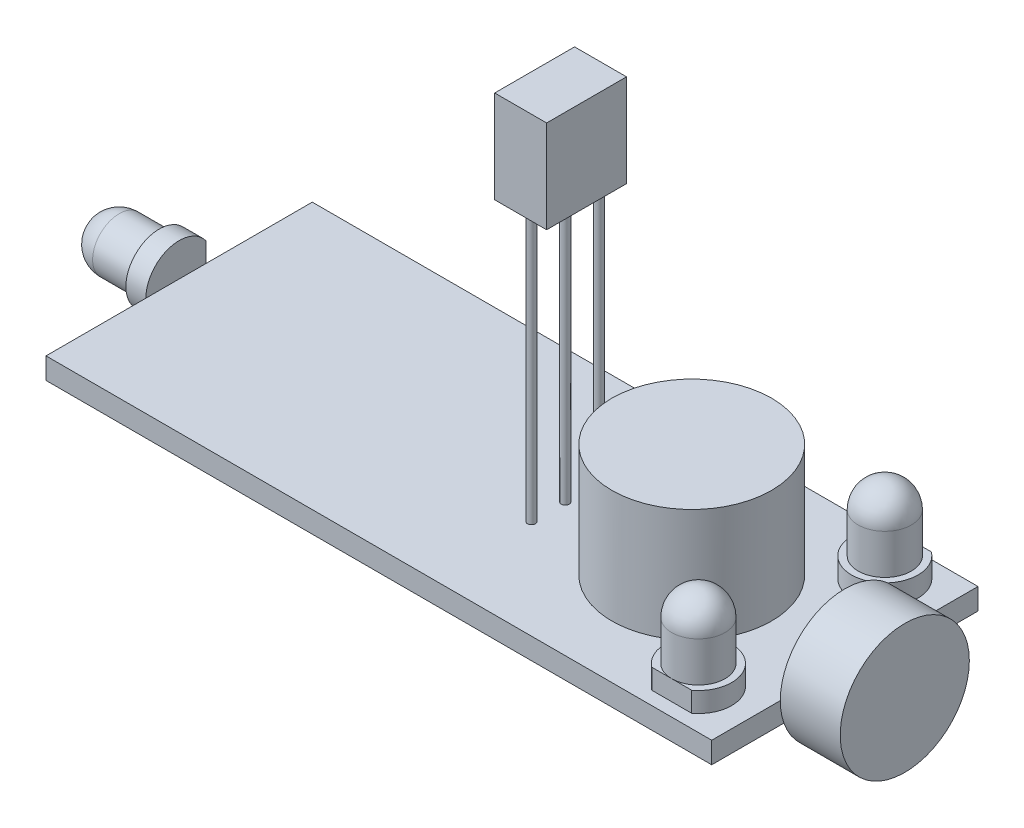
SolidWorks part; units mm, degrees
ref_plane "Front Plane" through (0, 0, 0) normal (0, 0, 1) x (1, 0, 0)
ref_plane "Top Plane" through (0, 0, 0) normal (0, 1, 0) x (1, 0, 0)
ref_plane "Right Plane" through (0, 0, 0) normal (1, 0, 0) x (0, 0, -1)
sketch "Sketch1" plane through (0, 0, 0) normal (0, 1, 0) x (1, 0, 0)
  line L1 (0, 0) -> (50, 0)
  line L2 (0, 0) -> (0, 20)
  line L3 (0, 20) -> (50, 20)
  line L4 (50, 0) -> (50, 20)
  dimension "D1" = 50
  dimension "D2" = 20
extrude "Boss-Extrude1" add sketch "Sketch1" along normal blind 1.6
sketch "Sketch2" plane through (0, 1.6, 0) normal (0, 1, 0) x (1, 0, 0)
  line L0 (50, 0) -> (50, 20) construction
  circle A0 centre (29, 12.54) radius 0.3
  circle A1 centre (29, 10) radius 0.3
  circle A2 centre (29, 7.46) radius 0.3
  point P6 (50, 10)
  dimension "D1" = 0.6
  dimension "D2" = 2.54
  dimension "D3" = 2.54
  dimension "D4" = 21
extrude "Boss-Extrude2" add sketch "Sketch2" along normal blind 20
sketch "Sketch3" plane through (0, 21.6, 0) normal (0, 1, 0) x (1, 0, 0)
  line L1 (26.7, 13) -> (30.6, 13)
  line L2 (26.7, 13) -> (26.7, 7)
  line L3 (26.7, 7) -> (30.6, 7)
  line L4 (30.6, 13) -> (30.6, 7)
  circle A0 centre (29, 12.54) radius 0.3 construction
  point P6 (26.7, 10)
  point P9 (29, 10)
  dimension "D1" = 1.6
  dimension "D2" = 3.9
  dimension "D3" = 6
extrude "Boss-Extrude3" add sketch "Sketch3" along normal blind 6.95
ref_plane "Plane1" through (0, 25.85, 0) normal (0, 1, 0) x (1, 0, 0)
sketch "Sketch5" plane through (0, 25.85, 0) normal (0, 1, 0) x (1, 0, 0)
  line L0 (26.7, 13) -> (26.7, 7) construction
  line L1 (30.6, 7) -> (30.6, 13) construction
  line L2 (25.4599, 10) -> (30.6, 10) construction
  line L3 (26.7, 12.5) -> (26.7, 10)
  line L4 (25.4599, 10) -> (26.7, 10)
  line L5 (26.7, 10) -> (26.7057, 9.9829)
  arc A0 (26.7, 12.5) -> (26.7, 7.5) centre (28.6, 10) ccw
  point P3 (30.6, 10)
  dimension "D1" = 2
  dimension "D2" = 5
revolve "Revolve1" add sketch "Sketch5" angle 360 about L2
sketch "Sketch6" plane through (0, 1.6, 0) normal (0, 1, 0) x (1, 0, 0)
  line L0 (50, 0) -> (50, 20) construction
  circle A0 centre (38.5, 10) radius 6
  point P4 (50, 10)
  dimension "D2" = 12
  dimension "D1" = 11.5
extrude "Boss-Extrude4" add sketch "Sketch6" along normal blind 8.5
sketch "Sketch7" plane through (50, 0, 0) normal (1, 0, 0) x (0, 0, -1)
  line L0 (0, 1.6) -> (20, 1.6) construction
  circle A0 centre (10, 1.6) radius 4.85
  dimension "D1" = 9.7
extrude "Boss-Extrude5" add sketch "Sketch7" along normal blind 4.5
sketch "Sketch8" plane through (0, 1.6, 0) normal (0, 1, 0) x (1, 0, 0)
  line L0 (50, 14.85) -> (50, 20) construction
  line L1 (50, 10) -> (0, 10) construction
  line L2 (50, 5.15) -> (50, 14.85) construction
  line L3 (0, 20) -> (0, 0) construction
  circle A0 centre (46, 17) radius 2.5
  dimension "D3" = 5
  dimension "D1" = 4
  dimension "D2" = 7
extrude "Boss-Extrude6" add sketch "Sketch8" along normal blind 1.5
sketch "Sketch9" plane through (0, 3.1, 0) normal (0, 1, 0) x (1, 0, 0)
  line L0 (46, 14.5) -> (46, 19.5) construction
  circle A0 centre (46, 17) radius 2.5 construction
  circle A1 centre (46, 17) radius 2.5 construction
  circle A2 centre (46, 17) radius 2.5 construction
  dimension "D1" = 5
ref_plane "Plane3" through (46, 0, 0) normal (1, 0, 0) x (0, 0, -1)
sketch "Sketch10" plane through (46, 0, 0) normal (1, 0, 0) x (0, 0, -1)
  line L0 (19, 3.1) -> (19, 6.1)
  line L1 (14.5, 3.1) -> (19.5, 3.1) construction
  line L2 (14.5, 3.1) -> (14.5, 1.6) construction
  line L3 (14.85, 1.6) -> (20, 1.6) construction
  line L4 (17, 3.1) -> (17, 8.1)
  line L5 (17, 3.1) -> (19, 3.1)
  arc A0 (19, 6.1) -> (17, 8.1) centre (17, 6.1) ccw
  point P4 (17, 3.1)
  dimension "D1" = 3
  dimension "D2" = 2.5
  dimension "D3" = 0.5
  dimension "D4" = 1.5
revolve "Revolve2" add sketch "Sketch10" angle 360 about L4
sketch "Sketch11" plane through (0, 1.6, 0) normal (0, 1, 0) x (1, 0, 0)
  line L0 (44.5, 19) -> (47.5, 19)
  circle A0 centre (46, 17) radius 2.5 construction
  arc A1 (44.5, 19) -> (47.5, 19) centre (46, 17) cw
  dimension "D1" = 3
extrude "Cut-Extrude1" cut sketch "Sketch11" along normal up to next
ref_plane "Plane2" through (0, 0, -10) normal (0, 0, 1) x (1, 0, 0)
mirror "Mirror1" about plane through (0, 0, -10) normal (0, 0, 1) of "Boss-Extrude6", "Revolve2", "Cut-Extrude1"
sketch "Sketch12" plane through (0, 0, 0) normal (-1, 0, 0) x (0, 0, 1)
  line L0 (-20, 1.6) -> (0, 1.6) construction
  line L1 (-12, 3.1) -> (-12, 0.1)
  circle A0 centre (-10, 1.6) radius 2.5
  line M1 (-20, 0) -> (0, 0)
  line M3 (0, 1.6) -> (-20, 1.6)
  dimension "D1" = 5
  dimension "D2" = 3
extrude "Boss-Extrude7" add sketch "Sketch12" along normal blind 1.5 contours A0 M1 | L1 A0 M1 M3 | A0 L1 M3
sketch "Sketch13" plane through (-1.5, 0, 0) normal (-1, 0, 0) x (0, 0, 1)
  line L0 (-10, 4.1) -> (-10, -0.9) construction
  arc A0 (-12, 0.1) -> (-12, 3.1) centre (-10, 1.6) ccw construction
ref_plane "Plane5" through (0, 0, -10) normal (0, 0, 1) x (1, 0, 0)
sketch "Sketch14" plane through (0, 0, -10) normal (0, 0, 1) x (1, 0, 0)
  line L0 (-1.5, 3.6) -> (-4.5, 3.6)
  line L1 (-1.5, 4.1) -> (-1.5, -0.9) construction
  line L2 (0, 4.1) -> (-1.5, 4.1) construction
  line L3 (-6.5, 1.6) -> (-1.5, 1.6)
  line L4 (-1.5, 3.6) -> (-1.5, 1.6)
  arc A0 (-4.5, 3.6) -> (-6.5, 1.6) centre (-4.5, 1.6) ccw
  dimension "D1" = 3
  dimension "D2" = 0.5
revolve "Revolve3" add sketch "Sketch14" angle 360 about L3
